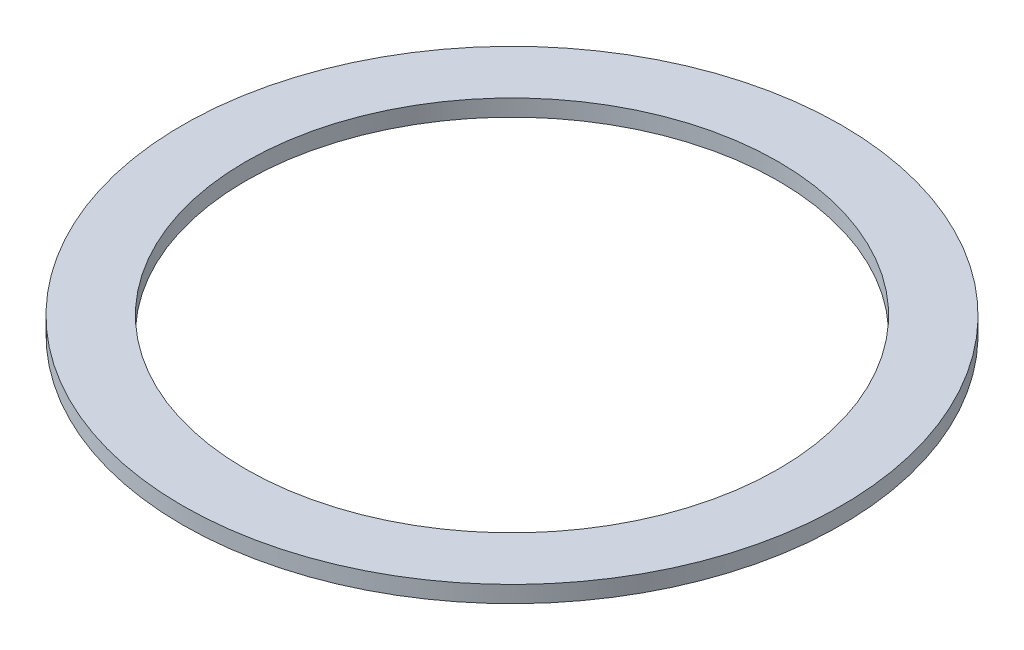
SolidWorks part; units mm, degrees
material "AISI 316 Annealed Stainless Steel Bar (SS)"
ref_plane "Front Plane" through (0, 0, 0) normal (0, 0, 1) x (1, 0, 0)
ref_plane "Top Plane" through (0, 0, 0) normal (0, 1, 0) x (1, 0, 0)
ref_plane "Right Plane" through (0, 0, 0) normal (1, 0, 0) x (0, 0, -1)
sketch "Sketch1" plane through (0, 0, 0) normal (0, 1, 0) x (1, 0, 0)
  circle A0 centre (0, 0) radius 62.865
  circle A1 centre (0, 0) radius 50.8
  dimension "D1" = 125.73
  dimension "D2" = 101.6
extrude "Boss-Extrude1" add sketch "Sketch1" along normal blind 3.175
